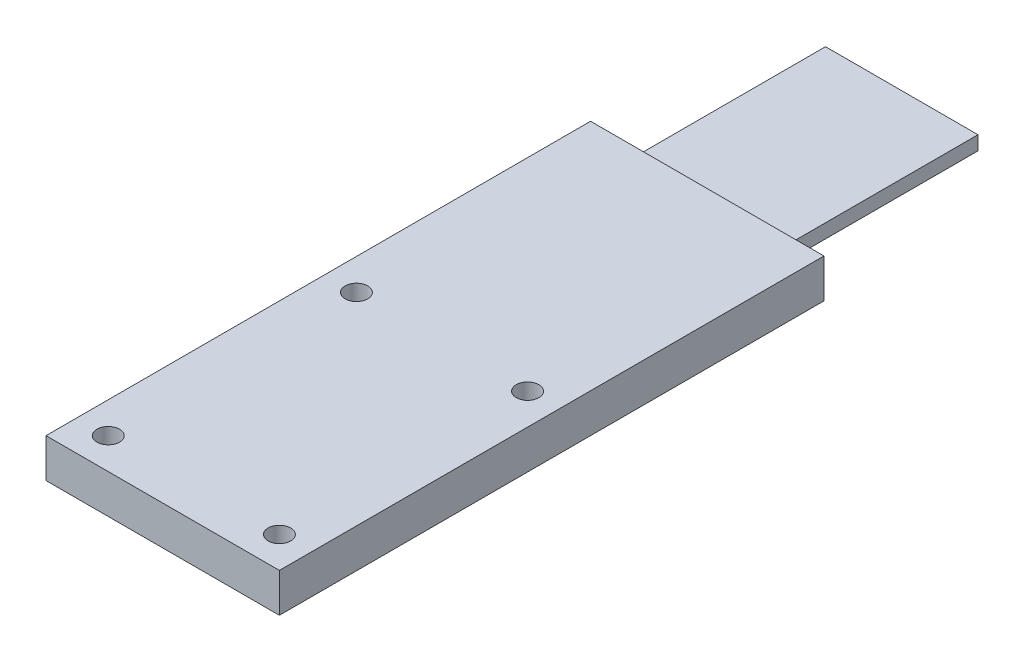
SolidWorks part; units mm, degrees
ref_plane "前视基准面" through (0, 0, 0) normal (0, 0, 1) x (1, 0, 0)
ref_plane "上视基准面" through (0, 0, 0) normal (0, 1, 0) x (1, 0, 0)
ref_plane "右视基准面" through (0, 0, 0) normal (1, 0, 0) x (0, 0, -1)
other "Configuration Table"
sketch "草图1" plane through (0, 0, 0) normal (0, 0, 1) x (1, 0, 0)
  line L1 (0, 0) -> (-30, 0)
  line L2 (0, 0) -> (0, 5)
  line L3 (0, 5) -> (-30, 5)
  line L4 (-30, 0) -> (-30, 5)
  dimension "D1" = 30
  dimension "D2" = 5
extrude "凸台-拉伸1" add sketch "草图1" along normal blind 70
sketch "草图2" plane through (0, 5, 0) normal (0, 1, 0) x (1, 0, 0)
  line L0 (-30, -70) -> (-26, -70) construction
  line L1 (0, -70) -> (-30, -70) construction
  line L2 (-26, -70) -> (-26, -66) construction
  line L3 (-26, -66) -> (-26, -34.1) construction
  line L4 (-15, -70) -> (-15, -30.41) construction
  circle A0 centre (-26, -66) radius 1.45
  circle A1 centre (-26, -34.1) radius 1.45
  circle A2 centre (-4, -66) radius 1.45
  circle A3 centre (-4, -34.1) radius 1.45
  dimension "D4" = 2.9
  dimension "D5" = 2.9
  dimension "D1" = 4
  dimension "D2" = 4
  dimension "D3" = 31.9
extrude "切除-拉伸1" cut sketch "草图2" against normal blind 60
sketch "草图3" plane through (0, 0, 0) normal (0, -1, 0) x (1, 0, 0)
  line L0 (0, 70) -> (0, 0) construction
  line L1 (-30, 0) -> (0, 0)
  line L2 (-30, 0) -> (-30, 10)
  line L3 (-30, 10) -> (0, 10)
  line L4 (0, 0) -> (0, 10)
  dimension "D1" = 10
sketch "草图4" plane through (0, 0, 0) normal (0, 0, -1) x (-1, 0, 0)
  line L0 (30, 5) -> (30, 0) construction
  line L1 (5.2, 3.4) -> (24.8, 3.4)
  line L2 (5.2, 3.4) -> (5.2, 1.6)
  line L3 (5.2, 1.6) -> (24.8, 1.6)
  line L4 (24.8, 3.4) -> (24.8, 1.6)
  line L5 (0, 0) -> (0, 5) construction
  line L6 (0, 5) -> (30, 5) construction
  line L7 (30, 0) -> (0, 0) construction
  dimension "D1" = 5.2
  dimension "D2" = 5.2
  dimension "D3" = 1.6
  dimension "D4" = 1.6
extrude "凸台-拉伸2" add sketch "草图4" along normal blind 25
